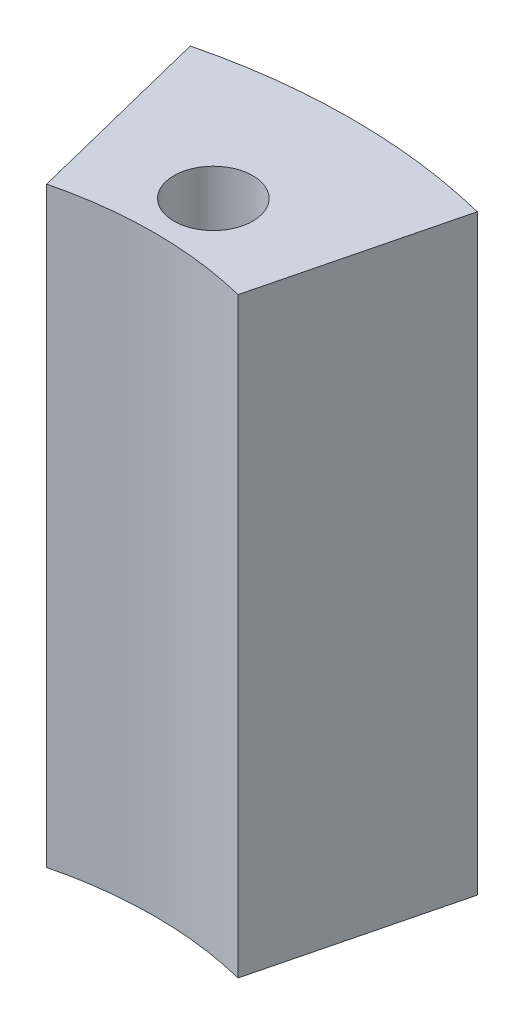
SolidWorks part; units mm, degrees
ref_plane "Front Plane" through (0, 0, 0) normal (0, 0, 1) x (1, 0, 0)
ref_plane "Top Plane" through (0, 0, 0) normal (0, 1, 0) x (1, 0, 0)
ref_plane "Right Plane" through (0, 0, 0) normal (1, 0, 0) x (0, 0, -1)
sketch "Sketch1" plane through (0, 0, 0) normal (0, 1, 0) x (1, 0, 0)
  line L0 (0, 0) -> (0, 22.9985) construction
  line L5 (-4.8507, 19.4029) -> (-7.2761, 29.1043)
  line L6 (4.8507, 19.4029) -> (7.2761, 29.1043)
  arc A0 (7.2761, 29.1043) -> (-7.2761, 29.1043) centre (0, 0) ccw
  arc A3 (4.8507, 19.4029) -> (-4.8507, 19.4029) centre (0, 0) ccw
  dimension "D1" = 60
  dimension "D5" = 40
extrude "Boss-Extrude2" add sketch "Sketch1" along normal blind 30
sketch "Sketch3" plane through (0, 0, 0) normal (0, -1, 0) x (1, 0, 0)
  line L0 (0, -23.0247) -> (0, -25.0247) construction
  circle A0 centre (0, -25.0247) radius 1.5
  dimension "D1" = 2
  dimension "D2" = 3
extrude "Cut-Extrude1" cut sketch "Sketch3" against normal blind 6
sketch "Sketch4" plane through (0, 30, 0) normal (0, 1, 0) x (1, 0, 0)
  line L0 (0, 20) -> (0, 23) construction
  arc A0 (4.8507, 19.4029) -> (-4.8507, 19.4029) centre (0, 0) ccw construction
  circle A1 centre (0, 23) radius 2
  dimension "D2" = 4
  dimension "D1" = 3
extrude "Cut-Extrude2" cut sketch "Sketch4" against normal blind 6
